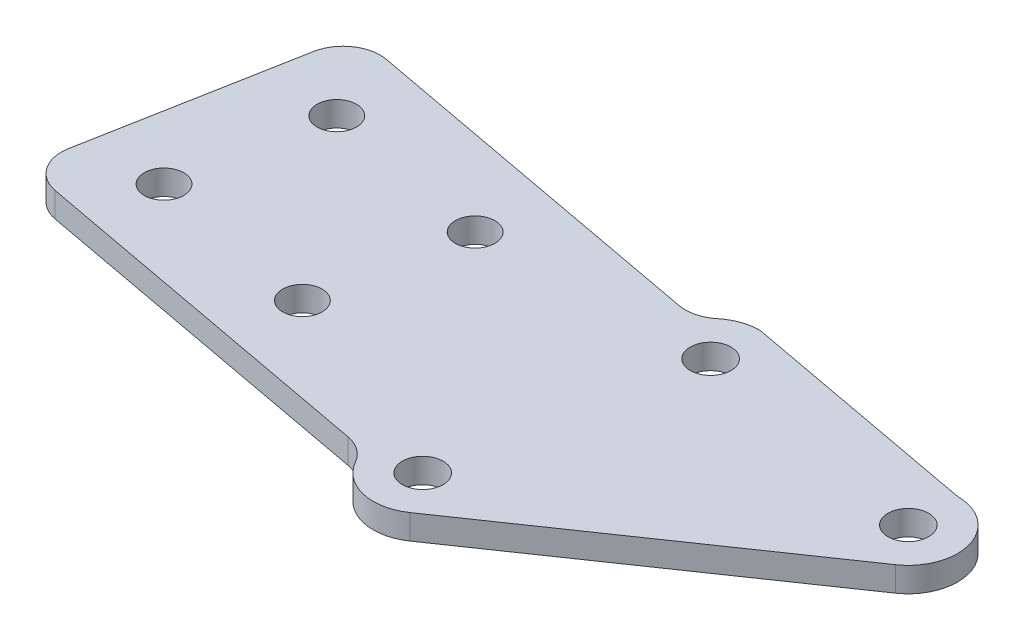
SolidWorks part; units mm, degrees
ref_plane "Front Plane" through (0, 0, 0) normal (0, 0, 1) x (1, 0, 0)
ref_plane "Top Plane" through (0, 0, 0) normal (0, 1, 0) x (1, 0, 0)
ref_plane "Right Plane" through (0, 0, 0) normal (1, 0, 0) x (0, 0, -1)
sketch "Sketch1" plane through (0, 0, 0) normal (0, 1, 0) x (1, 0, 0)
  line L0 (1.4975, 0.7868) -> (-36.9339, 98.5008) construction
  line L6 (-56.6569, 90.4835) -> (-36.9937, 86.8285)
  line L17 (-34.7298, 79.5308) -> (-58.048, 63.5226)
  line L18 (-61.6543, 88.9381) -> (-90.7933, 94.3545)
  line L19 (1.4975, 0.7868) -> (79.9099, 31.6269) construction
  line L20 (-94.291, 91.9533) -> (-97.3978, 75.2396)
  line L21 (-65.8576, 66.3255) -> (-94.9966, 71.7418)
  line L22 (6.159, 94.65) -> (23.8009, 118.4656) construction
  line L23 (9.5157, 132.7811) -> (23.176, 122.6619) construction
  line L24 (-12.3225, 108.3406) -> (5.3194, 132.1562) construction
  line L25 (-25.6246, 83.1119) -> (2.3512, 87.278) construction
  line L26 (-17.0338, 106.0675) -> (-28.9387, 89.9966) construction
  line L27 (59.6519, -88.9099) -> (39.9887, -85.2549) construction
  line L28 (37.7248, -77.9572) -> (61.043, -61.949) construction
  line L29 (64.6494, -87.3645) -> (93.7884, -92.7809) construction
  line L30 (97.2861, -90.3797) -> (100.3929, -73.666) construction
  line L31 (68.8527, -64.7518) -> (97.9916, -70.1682) construction
  line L32 (-3.1639, -93.0764) -> (-20.8058, -116.8919) construction
  line L33 (-6.5207, -131.2074) -> (-20.1809, -121.0883) construction
  line L34 (15.3176, -106.767) -> (-2.3243, -130.5825) construction
  line L35 (28.6196, -81.5383) -> (0.6438, -85.7043) construction
  line L36 (20.0288, -104.4939) -> (31.9337, -88.423) construction
  circle A33 centre (-56.6569, 86.4835) radius 1.65
  circle A34 centre (-36.9937, 82.8285) radius 1.65
  circle A35 centre (-40.6487, 63.1653) radius 1.65 construction
  circle A36 centre (-60.3119, 66.8203) radius 1.65
  arc A37 (-56.6569, 90.4835) -> (-59.1993, 89.5716) centre (-56.6569, 86.4835) ccw
  arc A38 (-34.7298, 79.5308) -> (-36.9937, 86.8285) centre (-36.9937, 82.8285) ccw
  arc A39 (-63.7941, 64.8521) -> (-58.048, 63.5226) centre (-60.3119, 66.8203) ccw
  arc A40 (-65.8576, 66.3255) -> (-63.7941, 64.8521) centre (-66.4058, 63.376) cw
  arc A41 (-59.1993, 89.5716) -> (-61.6543, 88.9381) centre (-61.1061, 91.8876) cw
  arc A42 (-90.7933, 94.3545) -> (-94.291, 91.9533) centre (-91.3416, 91.405) ccw
  arc A43 (-94.9966, 71.7418) -> (-97.3978, 75.2396) centre (-94.4483, 74.6913) cw
  arc A44 (23.8009, 118.4656) -> (23.176, 122.6619) centre (21.3903, 120.2513) ccw construction
  arc A45 (5.3194, 132.1562) -> (9.5157, 132.7811) centre (7.73, 130.3704) cw construction
  arc A46 (-14.5513, 107.1319) -> (-12.3225, 108.3406) centre (-14.7332, 110.1263) ccw construction
  arc A47 (6.159, 94.65) -> (5.6521, 92.1657) centre (8.5696, 92.8643) ccw construction
  arc A48 (5.6521, 92.1657) -> (2.3512, 87.278) centre (1.7621, 91.2343) cw construction
  arc A49 (-25.6246, 83.1119) -> (-28.9387, 89.9966) centre (-26.2137, 87.0683) cw construction
  arc A50 (-17.0338, 106.0675) -> (-14.5513, 107.1319) centre (-14.3088, 103.1392) cw construction
  circle A51 centre (1.7621, 91.2343) radius 1.65 construction
  circle A52 centre (-10.1428, 75.1634) radius 1.65 construction
  circle A53 centre (-26.2137, 87.0683) radius 1.65 construction
  circle A54 centre (-14.3088, 103.1392) radius 1.65 construction
  circle A55 centre (59.6519, -84.9099) radius 1.65 construction
  circle A56 centre (39.9887, -81.2549) radius 1.65 construction
  circle A57 centre (43.6437, -61.5917) radius 1.65 construction
  circle A58 centre (63.3069, -65.2467) radius 1.65 construction
  arc A59 (59.6519, -88.9099) -> (62.1943, -87.9979) centre (59.6519, -84.9099) ccw construction
  arc A60 (37.7248, -77.9572) -> (39.9887, -85.2549) centre (39.9887, -81.2549) ccw construction
  arc A61 (66.7892, -63.2785) -> (61.043, -61.949) centre (63.3069, -65.2467) ccw construction
  arc A62 (68.8527, -64.7518) -> (66.7892, -63.2785) centre (69.4009, -61.8024) cw construction
  arc A63 (62.1943, -87.9979) -> (64.6494, -87.3645) centre (64.1012, -90.314) cw construction
  arc A64 (93.7884, -92.7809) -> (97.2861, -90.3797) centre (94.3366, -89.8314) ccw construction
  arc A65 (97.9916, -70.1682) -> (100.3929, -73.666) centre (97.4434, -73.1177) cw construction
  arc A66 (-20.8058, -116.8919) -> (-20.1809, -121.0883) centre (-18.3952, -118.6777) ccw construction
  arc A67 (-2.3243, -130.5825) -> (-6.5207, -131.2074) centre (-4.7349, -128.7968) cw construction
  arc A68 (17.5464, -105.5582) -> (15.3176, -106.767) centre (17.7282, -108.5527) ccw construction
  arc A69 (-3.1639, -93.0764) -> (-2.657, -90.5921) centre (-5.5746, -91.2907) ccw construction
  arc A70 (-2.657, -90.5921) -> (0.6438, -85.7043) centre (1.233, -89.6607) cw construction
  arc A71 (28.6196, -81.5383) -> (31.9337, -88.423) centre (29.2088, -85.4947) cw construction
  arc A72 (20.0288, -104.4939) -> (17.5464, -105.5582) centre (17.3039, -101.5656) cw construction
  circle A73 centre (1.233, -89.6607) radius 1.65 construction
  circle A74 centre (13.1379, -73.5898) radius 1.65 construction
  circle A75 centre (29.2088, -85.4947) radius 1.65 construction
  circle A76 centre (17.3039, -101.5656) radius 1.65 construction
  dimension "D1" = 8
  dimension "D2" = 8
  dimension "D3" = 8
  dimension "D4" = 3
  dimension "D5" = 3
extrude "Boss-Extrude1" add sketch "Sketch1" along normal mid plane 2
sketch "Sketch7" plane through (0, 1, 0) normal (0, 1, 0) x (1, 0, 0)
  line L0 (-88.849, 88.3989) -> (-91.042, 76.601) construction
  line L1 (-94.291, 91.9533) -> (-97.3978, 75.2396) construction
  line L2 (-75.0847, 85.8404) -> (-77.2777, 74.0425) construction
  line L3 (-61.6543, 88.9381) -> (-90.7933, 94.3545) construction
  circle A0 centre (-88.849, 88.3989) radius 1.6
  circle A1 centre (-91.042, 76.601) radius 1.6
  circle A2 centre (-75.0847, 85.8404) radius 1.6
  circle A3 centre (-77.2777, 74.0425) radius 1.6
  dimension "D2" = 3.2
  dimension "D3" = 12
  dimension "D1" = 6
  dimension "D4" = 5.5
  dimension "D5" = 5.5
  dimension "D6" = 12
  dimension "D7" = 14
extrude "Cut-Extrude2" cut sketch "Sketch7" against normal blind 2
